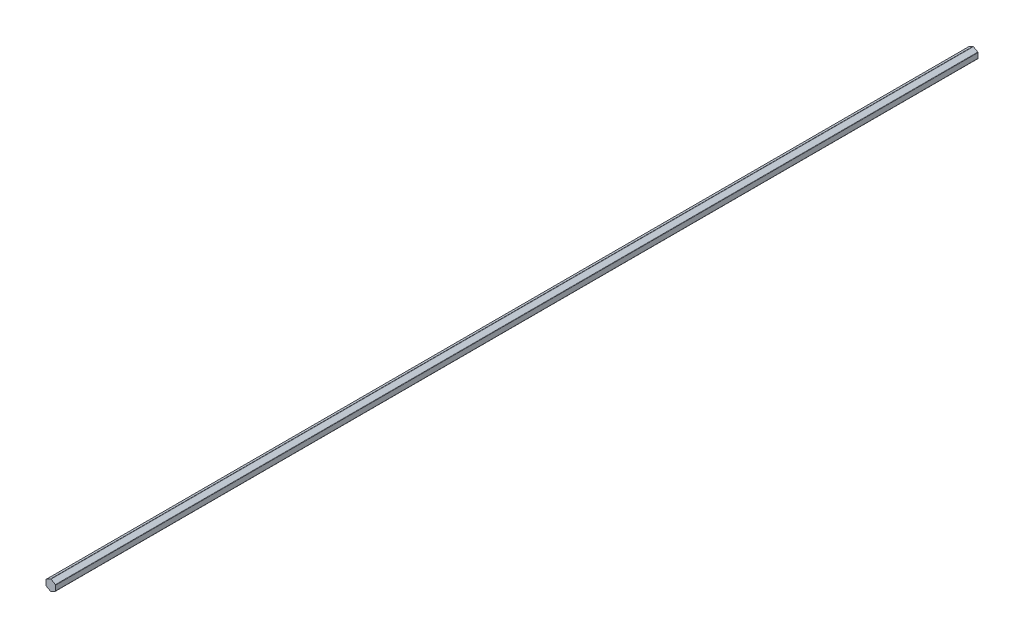
SolidWorks part; units mm, degrees
material "7075-T6 (SN)"
ref_plane "Front" through (0, 0, 0) normal (0, 0, 1) x (1, 0, 0)
ref_plane "Top" through (0, 0, 0) normal (0, 1, 0) x (1, 0, 0)
ref_plane "Right" through (0, 0, 0) normal (1, 0, 0) x (0, 0, -1)
sketch "Sketch1" plane through (0, 0, 0) normal (0, 0, 1) x (1, 0, 0)
  line L1 (0, 5.4993) -> (-4.7625, 2.7496)
  line L2 (-4.7625, 2.7496) -> (-4.7625, -2.7496)
  line L3 (-4.7625, -2.7496) -> (0, -5.4993)
  line L4 (0, -5.4993) -> (4.7625, -2.7496)
  line L5 (4.7625, -2.7496) -> (4.7625, 2.7496)
  line L6 (4.7625, 2.7496) -> (0, 5.4993)
  circle A0 centre (0, 0) radius 4.7625 construction
  dimension "D1" = 9.525
extrude "Shaft Boss" add sketch "Sketch1" along normal blind 914.4
fillet "Fillet1" radius 0.508 6 edges at (-4.7625, -2.7496, 457.2) (0, -5.4993, 457.2) (4.7625, -2.7496, 457.2) (-4.7625, 2.7496, 457.2) (0, 5.4993, 457.2) (4.7625, 2.7496, 457.2)
sketch "Sketch2" plane through (0, 0, 0) normal (0, 0, -1) x (-1, 0, 0)
  circle A0 centre (0, 0) radius 5.1245
  circle A1 centre (0, 0) radius 7.6645
  dimension "D1" = 10.2489
  dimension "D2" = 2.54
extrude "Cut For Thunder Hex Round" [suppressed] cut sketch "Sketch2" against normal blind 914.4
sketch "Sketch3" plane through (0, 0, 0) normal (0, 0, -1) x (-1, 0, 0)
  circle A0 centre (0, 0) radius 2.0955
  dimension "D1" = 4.191
extrude "Center Hole Cut" [suppressed] cut sketch "Sketch3" against normal blind 914.4
equation "\"HS\"=3 / 8"
equation "\"L\"= 36"
equation "\"D1@Sketch1\"=\"HS\""
equation "\"D1@Shaft Boss\" = \"L\""
equation "\"THOD\"=.4035"
equation "\"Fillet1\"    = \"suppressed\""
equation "\"Shaft Boss\"= \"unsuppressed\""
equation "\"D1@Sketch2\"=\"THOD\""
equation "\"D1@Cut For Thunder Hex Round\" = \"L\""
equation "\"Cut For Thunder Hex Round\"  = \"unsuppressed\""
equation "\"THID\"=.165"
equation "\"D1@Sketch3\"=\"THID\""
equation "\"D1@Center Hole Cut\" = \"L\""
equation "\"Center Hole Cut\"   = \"unsuppressed\""
